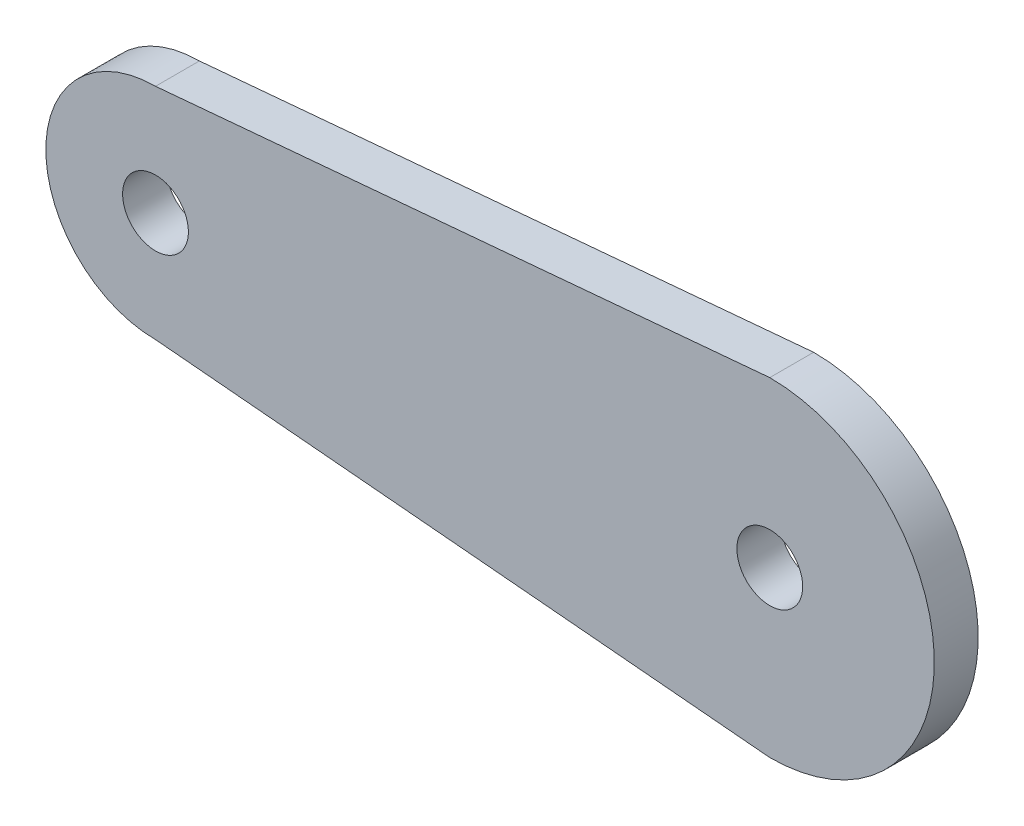
SolidWorks part; units mm, degrees
ref_plane "Front Plane" through (0, 0, 0) normal (0, 0, 1) x (1, 0, 0)
ref_plane "Top Plane" through (0, 0, 0) normal (0, 1, 0) x (1, 0, 0)
ref_plane "Right Plane" through (0, 0, 0) normal (1, 0, 0) x (0, 0, -1)
sketch "Sketch1" plane through (0, 0, 0) normal (0, 0, 1) x (1, 0, 0)
  line L0 (0, 0) -> (28, 0) construction
  line L1 (0, 5) -> (0, -5) construction
  line L2 (28, 7.5) -> (28, -7.5) construction
  line L3 (0, 5) -> (28, 7.5)
  line L4 (0, -5) -> (28, -7.5)
  circle A0 centre (0, 0) radius 1.5
  circle A1 centre (28, 0) radius 1.5
  arc A2 (0, 5) -> (0, -5) centre (0, 0) ccw
  arc A3 (28, 7.5) -> (28, -7.5) centre (28, 0) cw
  dimension "D5" = 5
  dimension "D6" = 3
  dimension "D7" = 3
  dimension "D1" = 28
  dimension "D2" = 10
  dimension "D3" = 15
  dimension "D4" = 7.5
extrude "Boss-Extrude1" add sketch "Sketch1" along normal blind 16 contours A3 L3 A2 L4 A1 A0
ref_plane "Plane1" through (0, 7.5, 0) normal (0, 1, 0) x (1, 0, 0)
sketch "Sketch3" plane through (0, 7.5, 0) normal (0, 1, 0) x (1, 0, 0)
  line L1 (41.5858, -2) -> (-6.9747, -2)
  line L2 (41.5858, -2) -> (41.5858, -14)
  line L3 (41.5858, -14) -> (-6.9747, -14)
  line L4 (-6.9747, -2) -> (-6.9747, -14)
  line L5 (-1.5, -16) -> (1.5, -16) construction
  dimension "D1" = 12
  dimension "D2" = 2
extrude "Cut-Extrude1" cut sketch "Sketch3" against normal through all
sketch "Sketch4" plane through (0, 0, 0) normal (0, 0, -1) x (-1, 0, 0)
  line L1 (6.8693, -8.5623) -> (-36.3397, -8.5623)
  line L2 (6.8693, -8.5623) -> (6.8693, 8.3525)
  line L3 (6.8693, 8.3525) -> (-36.3397, 8.3525)
  line L4 (-36.3397, -8.5623) -> (-36.3397, 8.3525)
extrude "Cut-Extrude2" cut sketch "Sketch4" against normal blind 10
